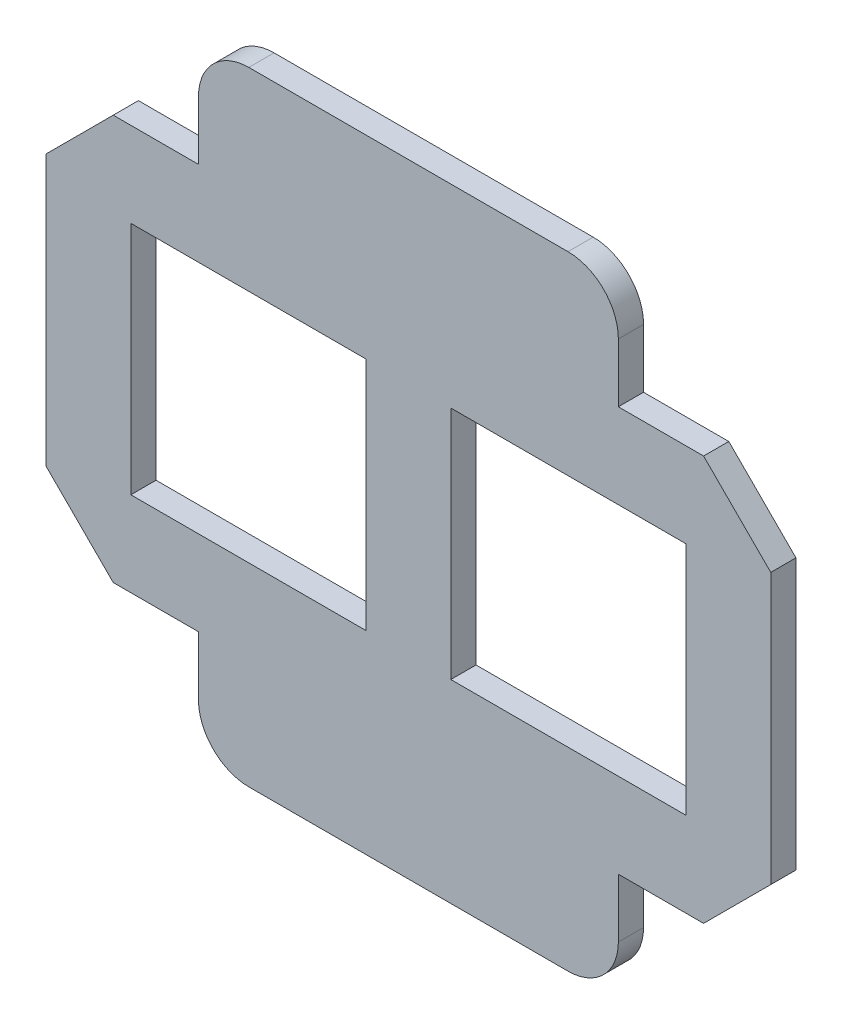
SolidWorks part; units mm, degrees
ref_plane "Front Plane" through (0, 0, 0) normal (0, 0, 1) x (1, 0, 0)
ref_plane "Top Plane" through (0, 0, 0) normal (0, 1, 0) x (1, 0, 0)
ref_plane "Right Plane" through (0, 0, 0) normal (1, 0, 0) x (0, 0, -1)
sketch "Sketch1" plane through (0, 0, 0) normal (0, 0, 1) x (1, 0, 0)
  line L0 (4.025, 19.05) -> (4.025, 25.55)
  line L1 (0, 0) -> (14, 0)
  line L2 (0, 0) -> (0, 14)
  line L3 (0, 14) -> (14, 14)
  line L4 (14, 0) -> (14, 14)
  line L5 (19.05, 0) -> (33.05, 0)
  line L6 (19.05, 0) -> (19.05, 14)
  line L7 (19.05, 14) -> (33.05, 14)
  line L8 (33.05, 0) -> (33.05, 14)
  line L9 (-5.05, 19.05) -> (38.1, 19.05)
  line L10 (-5.05, 19.05) -> (-5.05, -5.05)
  line L11 (-5.05, -5.05) -> (38.1, -5.05)
  line L12 (38.1, 19.05) -> (38.1, -5.05)
  line L13 (4.025, 25.55) -> (29.025, 25.55)
  line L14 (29.025, 25.55) -> (29.025, 19.05)
  line L16 (4.025, -5.05) -> (29.025, -5.05)
  line L17 (4.025, -5.05) -> (4.025, -11.55)
  line L18 (4.025, -11.55) -> (29.025, -11.55)
  line L19 (29.025, -5.05) -> (29.025, -11.55)
  point P21 (16.525, -11.55)
  point P22 (16.525, -5.05)
  dimension "D1" = 14
  dimension "D2" = 19.05
  dimension "D3" = 5.05
  dimension "D4" = 5.05
  dimension "D5" = 5.05
  dimension "D6" = 5.05
  dimension "D7" = 5.05
  dimension "D8" = 6.5
  dimension "D9" = 6.5
  dimension "D10" = 25
  dimension "D11" = 25
extrude "Boss-Extrude1" add sketch "Sketch1" along normal blind 1.5 contours L14 L13 L0 L9 | L12 L9 L10 L11 L8 L5 L6 L7 L4 L1 L2 L3 | L19 L11 L17 L18
fillet "Fillet1" radius 3 4 edges at (4.025, -11.55, 0.75) (29.025, -11.55, 0.75) (29.025, 25.55, 0.75) (4.025, 25.55, 0.75)
chamfer "Chamfer1" distance 4 angle 45 4 edges at (38.1, -5.05, 0.75) (38.1, 19.05, 0.75) (-5.05, -5.05, 0.75) (-5.05, 19.05, 0.75)
equation "\"D4@Sketch1\"=\"D3@Sketch1\""
equation "\"D5@Sketch1\"=\"D4@Sketch1\""
equation "\"D6@Sketch1\"=\"D4@Sketch1\""
equation "\"D7@Sketch1\"=\"D4@Sketch1\""
